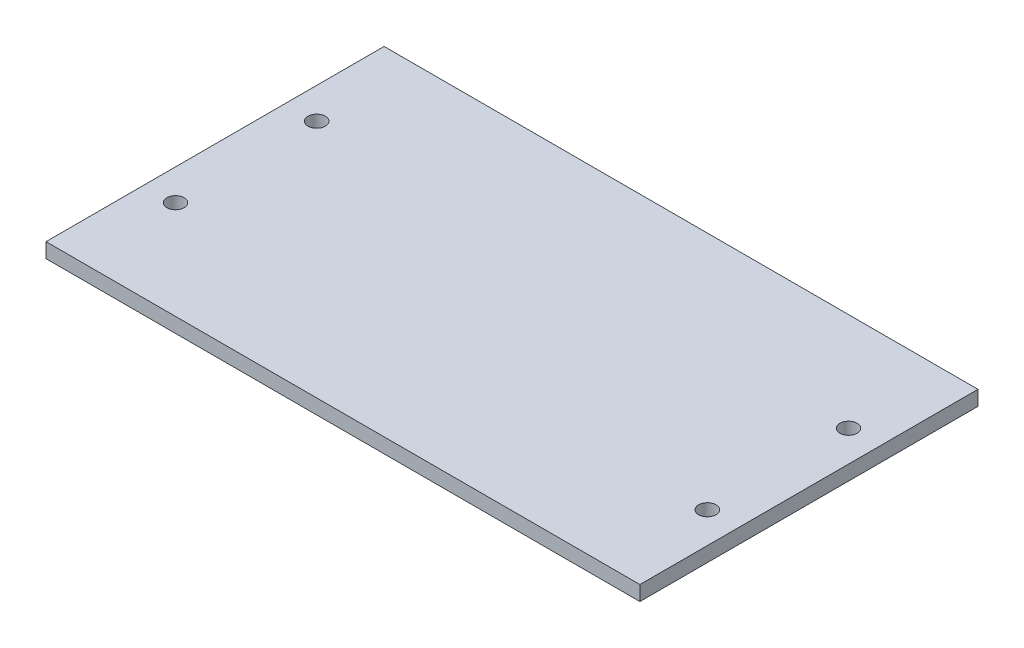
SolidWorks part; units mm, degrees
material "Acrylic (Medium-high impact)"
ref_plane "Front Plane" through (0, 0, 0) normal (0, 0, 1) x (1, 0, 0)
ref_plane "Top Plane" through (0, 0, 0) normal (0, 1, 0) x (1, 0, 0)
ref_plane "Right Plane" through (0, 0, 0) normal (1, 0, 0) x (0, 0, -1)
sketch "Sketch1" plane through (0, 0, 0) normal (0, 1, 0) x (1, 0, 0)
  line L1 (0, 0) -> (191.516, 0)
  line L2 (0, 0) -> (0, 109.0295)
  line L3 (0, 109.0295) -> (191.516, 109.0295)
  line L4 (191.516, 0) -> (191.516, 109.0295)
  circle A0 centre (10.0076, 77.2795) radius 2.794
  circle A1 centre (10.0076, 31.75) radius 2.794
  circle A2 centre (181.5084, 77.2795) radius 2.794
  circle A3 centre (181.5084, 31.75) radius 2.794
  dimension "D3" = 5.588
  dimension "D4" = 5.588
  dimension "D5" = 5.588
  dimension "D6" = 5.588
  dimension "D1" = 109.0295
  dimension "D2" = 191.516
  dimension "D7" = 10.0076
  dimension "D8" = 10.0076
  dimension "D9" = 10.0076
  dimension "D10" = 10.0076
  dimension "D11" = 31.75
  dimension "D12" = 31.75
  dimension "D13" = 31.75
  dimension "D14" = 31.75
extrude "Boss-Extrude1" add sketch "Sketch1" along normal blind 4.7625
